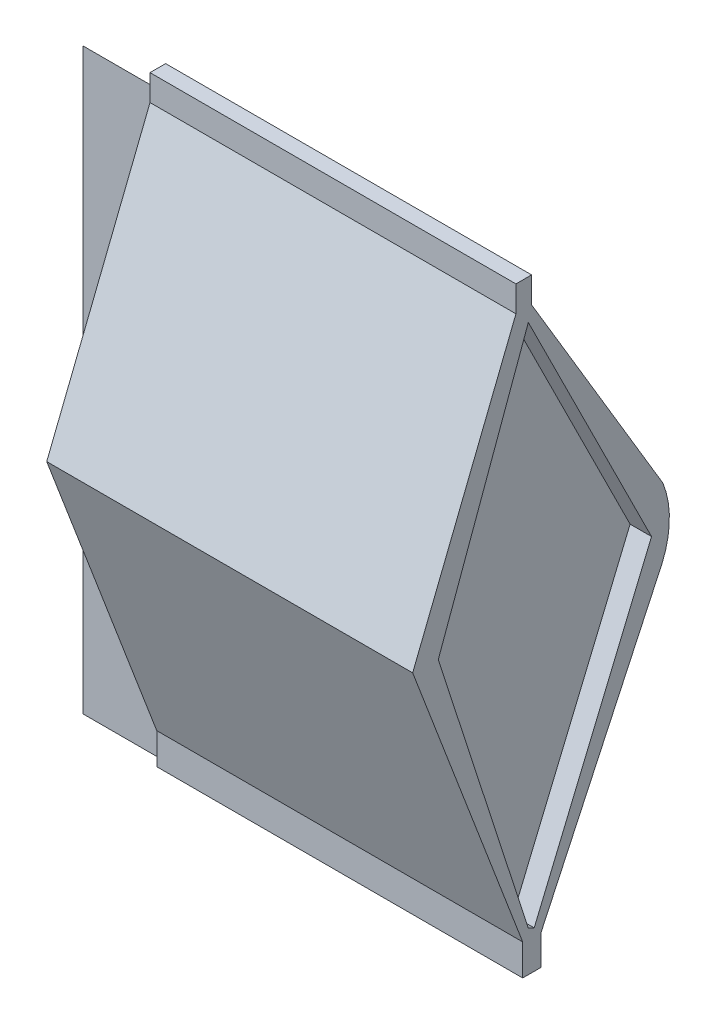
SolidWorks part; units mm, degrees
ref_plane "Front Plane" through (0, 0, 0) normal (0, 0, 1) x (1, 0, 0)
ref_plane "Top Plane" through (0, 0, 0) normal (0, 1, 0) x (1, 0, 0)
ref_plane "Right Plane" through (0, 0, 0) normal (1, 0, 0) x (0, 0, -1)
sketch "Sketch4" plane through (0, 0, 0) normal (0, 0, 1) x (1, 0, 0)
  line L1 (-31.4181, 42.3611) -> (31.4181, 42.3611)
  line L2 (-31.4181, 42.3611) -> (-31.4181, -42.3611)
  line L3 (-31.4181, -42.3611) -> (31.4181, -42.3611)
  line L4 (31.4181, 42.3611) -> (31.4181, -42.3611)
  line L5 (-31.4181, 42.3611) -> (31.4181, -42.3611) construction
  line L6 (-31.4181, -42.3611) -> (31.4181, 42.3611) construction
  point P0 (0, 0)
extrude "Boss-Extrude2" add sketch "Sketch4" along normal blind 50
sketch "Sketch5" plane through (31.4181, 0, 0) normal (1, 0, 0) x (0, 0, -1)
  line L0 (-31.846, 42.3611) -> (-33.6642, 67.8538)
  line L1 (-50, 42.3611) -> (0, 42.3611) construction
  line L2 (-46.3223, 2.3889) -> (-30.8984, -37.9824)
  line L3 (-30.8984, -37.9824) -> (-30.8984, -42.3611)
  line L4 (-50, -42.3611) -> (0, -42.3611) construction
  line L6 (-29.0687, -42.3611) -> (-29.0687, -37.9824)
  line L7 (-29.0687, -37.9824) -> (-13.2397, 2.3889)
  line L8 (-13.2397, 2.3889) -> (-28.1509, 38.7282)
  line L9 (-28.1509, 38.7282) -> (-28.1509, 42.3611)
  line L11 (-31.846, 42.3611) -> (-31.846, 38.7282)
  line L12 (-31.846, 38.7282) -> (-46.3223, 2.3889)
  line L13 (-33.6642, 67.8538) -> (-71.791, 67.8538)
  line L14 (-71.791, 67.8538) -> (-78.4638, -46.7769)
  line L15 (-78.4638, -46.7769) -> (-30.8035, -45.1607)
  line L16 (-30.8035, -45.1607) -> (-30.8984, -42.3611)
  line M12 (0, 42.3611) -> (-50, 42.3611)
  line M13 (-50, 42.3611) -> (-50, -42.3611)
  line M14 (-50, -42.3611) -> (0, -42.3611)
extrude "Cut-Extrude2" cut sketch "Sketch5" against normal blind 80 contours L12 L11 L3 L2 M12 M13 M14
sketch "Sketch6" plane through (31.4181, 0, 0) normal (1, 0, 0) x (0, 0, -1)
  line L0 (-29.6554, 42.3611) -> (-29.6554, 38.7226)
  line L1 (-31.846, 42.3611) -> (0, 42.3611) construction
  line L2 (-29.6554, 38.7226) -> (-8.7764, 3.7502)
  line L3 (-8.7764, 3.7502) -> (-28.3285, -38.1177)
  line L4 (-28.3285, -38.1177) -> (-28.3285, -42.3611)
  line L5 (-30.8984, -42.3611) -> (0, -42.3611) construction
  line L6 (-28.3285, -42.3611) -> (-27.6775, -46.6259)
  line L7 (-27.6775, -46.6259) -> (16.8398, -52.0454)
  line L8 (16.8398, -52.0454) -> (10.2677, 27.1903)
  line L9 (10.2677, 27.1903) -> (3.7395, 54.484)
  line L10 (3.7395, 54.484) -> (-29.6554, 42.3611)
extrude "Cut-Extrude3" cut sketch "Sketch6" against normal blind 80
sketch "Sketch7" plane through (-31.4181, 0, 0) normal (-1, 0, 0) x (0, 0, 1)
  line L1 (29.6554, 38.7226) -> (8.7764, 3.7502) construction
  line L2 (8.7764, 3.7502) -> (28.3285, -38.1177) construction
  arc A0 (13.2289, 11.2081) -> (11.7109, -2.5336) centre (22.9458, 3.18) ccw
  arc A1 (13.2289, 11.2081) -> (11.7109, -2.5336) centre (8.6224, 4.7623) ccw
extrude "Cut-Extrude5" cut sketch "Sketch7" against normal blind 80
sketch "Sketch8" plane through (31.4181, 0, 0) normal (1, 0, 0) x (0, 0, -1)
  line L0 (-30.1116, 36.8174) -> (-42.7351, 2.196)
  line L1 (-42.7351, 2.196) -> (-30.1116, -36.6941)
  line L2 (-30.1116, -36.6941) -> (-29.2891, -37.0782)
  line L3 (-29.2891, -37.0782) -> (-12.8456, 2.196)
  line L4 (-12.8456, 2.196) -> (-30.1116, 36.8174)
extrude "Cut-Extrude6" cut sketch "Sketch8" against normal blind 3
sketch "Sketch9" plane through (0, 0, 29.6554) normal (0, 0, -1) x (-1, 0, 0)
  line L0 (19.8699, 42.3611) -> (19.8699, 38.7226)
  line L1 (31.4181, 42.3611) -> (-31.4181, 42.3611) construction
  line L2 (31.4181, 38.7226) -> (-31.4181, 38.7226) construction
  line L3 (19.8699, 38.7226) -> (19.8699, 5.587)
  line L4 (19.8699, 5.587) -> (19.8699, -4.1869)
  line L5 (19.8699, -4.1869) -> (19.8699, -38.2085)
  line L6 (19.8699, -38.2085) -> (19.8699, -42.0598)
  line L7 (19.8699, -42.0598) -> (19.8699, -47.0269)
  line L8 (19.8699, -47.0269) -> (41.2567, -49.5859)
  line L9 (41.2567, -49.5859) -> (42.0813, -21.1977)
  line L10 (42.0813, -21.1977) -> (42.0813, 12.4282)
  line L11 (42.0813, 12.4282) -> (37.4822, 37.5131)
  line L12 (37.4822, 37.5131) -> (31.4181, 49.4838)
  line L13 (31.4181, 49.4838) -> (19.8699, 42.3611)
extrude "Cut-Extrude8" cut sketch "Sketch9" against normal blind 80
sketch "Sketch10" plane through (0, -2.8774, 4.8197) normal (0, 0.5126, -0.8586) x (-1, 0, 0)
  line L0 (19.8699, 48.4497) -> (25.6937, -39.8033)
  line L1 (25.6937, -39.8033) -> (32.4481, -43.4448)
  line L2 (32.4481, -43.4448) -> (49.8026, -43.4448)
  line L3 (49.8026, -43.4448) -> (32.4481, 57.8409)
  line L4 (32.4481, 57.8409) -> (19.8699, 48.4497)
